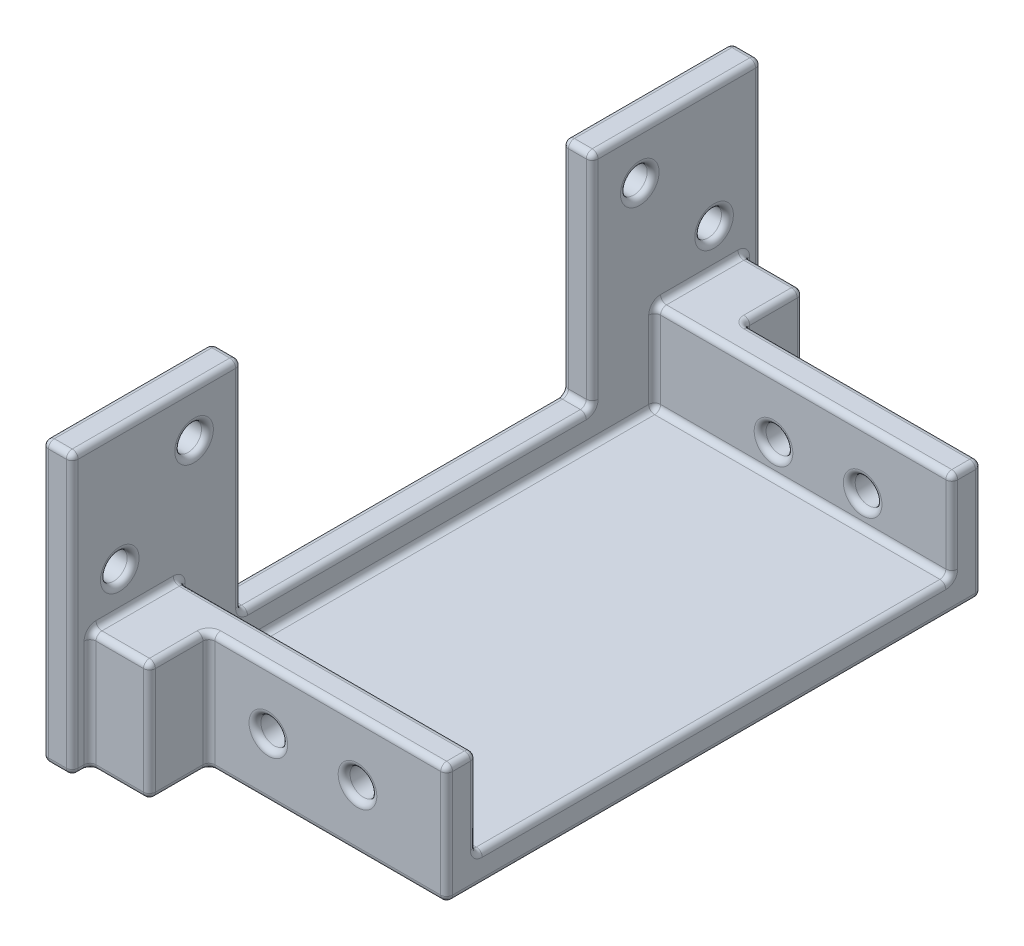
SolidWorks part; units mm, degrees
ref_plane "Front Plane" through (0, 0, 0) normal (0, 0, 1) x (1, 0, 0)
ref_plane "Top Plane" through (0, 0, 0) normal (0, 1, 0) x (1, 0, 0)
ref_plane "Right Plane" through (0, 0, 0) normal (1, 0, 0) x (0, 0, -1)
sketch "Sketch1" plane through (0, 0, 0) normal (1, 0, 0) x (0, 0, -1)
  line L1 (-38.6935, 11.3449) -> (-10.1935, 11.3449)
  line L2 (-38.6935, 11.3449) -> (-38.6935, -35.6551)
  line L3 (-38.6935, -35.6551) -> (77.3065, -35.6551)
  line L4 (77.3065, 11.3449) -> (77.3065, -35.6551)
  line L7 (48.8065, 11.3449) -> (77.3065, 11.3449)
  line L8 (-10.1935, 11.3449) -> (-10.1935, -25.6551)
  line L10 (-10.1935, -25.6551) -> (48.8065, -25.6551)
  line L12 (48.8065, -25.6551) -> (48.8065, 11.3449)
  circle A0 centre (-30.6935, -9.1551) radius 2.25
  circle A1 centre (-18.1935, 3.3449) radius 2.25
  circle A2 centre (69.3065, -9.1551) radius 2.25
  circle A3 centre (56.8065, 3.3449) radius 2.25
  dimension "D3" = 8
  dimension "D4" = 4.5
  dimension "D5" = 8
  dimension "D6" = 8
  dimension "D2" = 39
  dimension "D7" = 100
  dimension "D8" = 75
  dimension "D9" = 8
  dimension "D10" = 12.5
  dimension "D11" = 8
  dimension "D12" = 10
  dimension "D14" = 12.5
extrude "Boss-Extrude1" add sketch "Sketch1" along normal blind 5
sketch "Sketch2" plane through (5, 0, 0) normal (1, 0, 0) x (0, 0, -1)
  line L0 (-38.6935, 11.3449) -> (-38.6935, -35.6551) construction
  line L1 (-25.6935, -35.6551) -> (64.3065, -35.6551)
  line L5 (-38.6935, -35.6551) -> (77.3065, -35.6551) construction
  line L6 (77.3065, -35.6551) -> (77.3065, 11.3449) construction
  line L7 (-20.6935, -30.6551) -> (59.3065, -30.6551)
  line L10 (-25.6935, -15.6551) -> (-20.6935, -15.6551)
  line L11 (-20.6935, -30.6551) -> (-20.6935, -15.6551)
  line L14 (64.3065, -15.6551) -> (59.3065, -15.6551)
  line L15 (59.3065, -30.6551) -> (59.3065, -15.6551)
  line L16 (-25.6935, -15.6551) -> (-25.6935, -35.6551)
  line L17 (64.3065, -35.6551) -> (64.3065, -15.6551)
  dimension "D1" = 5
  dimension "D2" = 13
  dimension "D3" = 5
  dimension "D4" = 13
  dimension "D5" = 15
extrude "Boss-Extrude2" add sketch "Sketch2" along normal blind 50
sketch "Sketch8" plane through (5, 0, 0) normal (1, 0, 0) x (0, 0, -1)
  line L0 (-38.6935, -35.6551) -> (-25.6935, -35.6551) construction
  line L1 (-25.6935, -15.6551) -> (-35.6935, -15.6551)
  line L2 (-25.6935, -15.6551) -> (-25.6935, -35.6551)
  line L3 (-25.6935, -35.6551) -> (-35.6935, -35.6551)
  line L4 (-35.6935, -15.6551) -> (-35.6935, -35.6551)
  line L5 (64.3065, -35.6551) -> (77.3065, -35.6551) construction
  line L6 (64.3065, -15.6551) -> (74.3065, -15.6551)
  line L7 (64.3065, -15.6551) -> (64.3065, -35.6551)
  line L8 (64.3065, -35.6551) -> (74.3065, -35.6551)
  line L9 (74.3065, -15.6551) -> (74.3065, -35.6551)
  dimension "D1" = 10
extrude "Boss-Extrude3" add sketch "Sketch8" along normal blind 10
sketch "Sketch9" plane through (0, 0, 25.6935) normal (0, 0, 1) x (1, 0, 0)
  line L0 (15, -35.6551) -> (15, -15.6551) construction
  line L6 (55, -15.6551) -> (15, -15.6551) construction
  circle A0 centre (25, -25.6551) radius 2.25
  circle A1 centre (40, -25.6551) radius 2.25
  dimension "D3" = 4.5
  dimension "D1" = 10
  dimension "D2" = 10
  dimension "D4" = 15
extrude "Cut-Extrude4" cut sketch "Sketch9" against normal blind 110
fillet "Fillet5" radius 1 76 edges at (2.5, -35.6551, -77.3065) (0, -35.6551, -19.3065) (2.5, -35.6551, 38.6935) (5, -35.6551, 37.1935) (10, -35.6551, 35.6935) (15, -35.6551, 30.6935) (35, -35.6551, 25.6935) (55, -35.6551, -19.3065) (35, -35.6551, -64.3065) (15, -35.6551, -69.3065) (10, -35.6551, -74.3065) (5, -35.6551, -75.8065) (0, 3.3449, -59.0565) (0, -9.1551, -71.5565) (0, 3.3449, 15.9435) (0, -9.1551, 28.4435) (0, -12.1551, -77.3065) (0, 11.3449, -63.0565) (0, -7.1551, -48.8065) (0, -25.6551, -19.3065) (0, -7.1551, 10.1935) (0, 11.3449, 24.4435) (0, -12.1551, 38.6935) (5, -25.6551, -74.3065) (5, -23.1551, -59.3065) (5, -23.1551, 20.6935) (5, -25.6551, 35.6935) (2.5, 11.3449, 10.1935) (5, 11.3449, 24.4435) (2.5, 11.3449, 38.6935) (2.5, 11.3449, -77.3065) (5, 11.3449, -63.0565) (2.5, 11.3449, -48.8065) (10, -15.6551, -74.3065) (15, -15.6551, -69.3065) (35, -15.6551, -64.3065) (30, -15.6551, -59.3065) (5, -15.6551, -66.8065) (30, -15.6551, 20.6935) (35, -15.6551, 25.6935) (15, -15.6551, 30.6935) (10, -15.6551, 35.6935) (5, -15.6551, 28.1935) (55, -15.6551, 23.1935) (55, -23.1551, 20.6935) (55, -30.6551, -19.3065) (55, -23.1551, -59.3065) (55, -15.6551, -61.8065) (55, -25.6551, -64.3065) (55, -25.6551, 25.6935) (2.5, -25.6551, -48.8065) (2.5, -25.6551, 10.1935) (5, -7.1551, 10.1935) (5, -25.6551, -19.3065) (5, -7.1551, -48.8065) (5, -12.1551, -77.3065) (5, -12.1551, 38.6935) (5, -9.1551, 28.4435) (5, 3.3449, 15.9435) (5, -9.1551, -71.5565) (5, 3.3449, -59.0565) (30, -30.6551, -59.3065) (30, -30.6551, 20.6935) (5, -30.6551, -19.3065) (15, -25.6551, 35.6935) (15, -25.6551, 25.6935) (15, -25.6551, -64.3065) (15, -25.6551, -74.3065) (27.25, -25.6551, -64.3065) (22.75, -25.6551, -59.3065) (27.25, -25.6551, 20.6935) (42.25, -25.6551, -64.3065) (37.75, -25.6551, -59.3065) (42.25, -25.6551, 20.6935) (27.25, -25.6551, 25.6935) (42.25, -25.6551, 25.6935)
